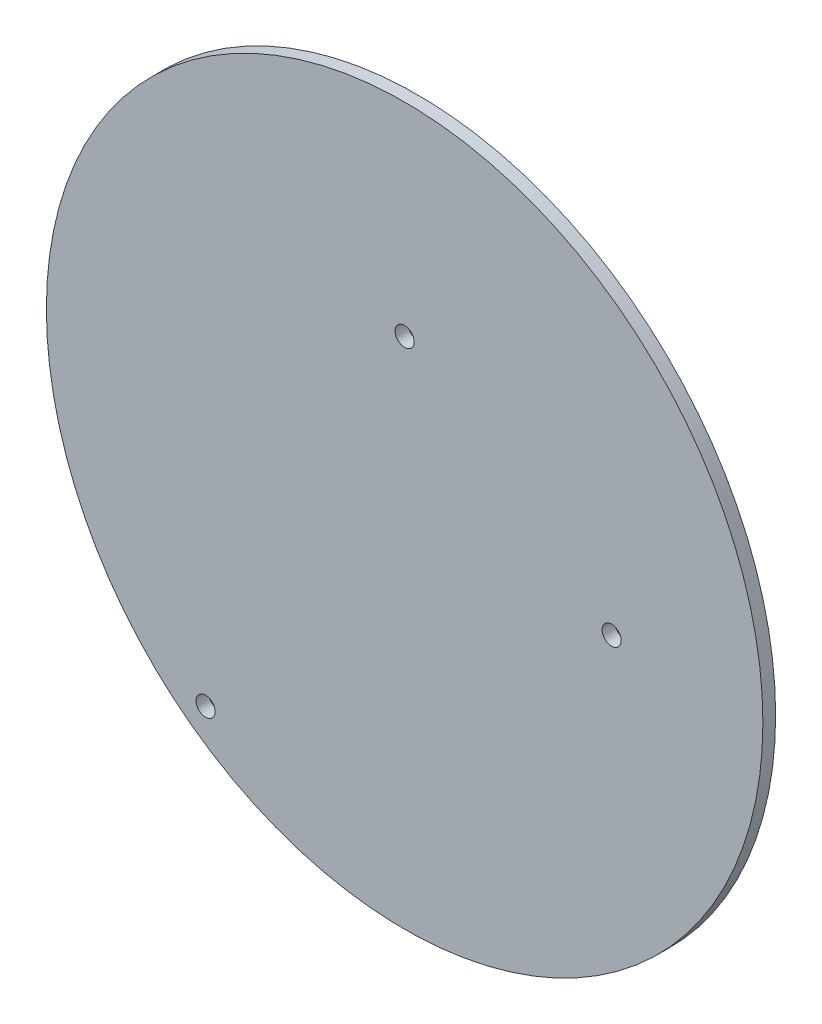
SolidWorks part; units mm, degrees
ref_plane "Front Plane" through (0, 0, 0) normal (1, 0, 0) x (0, 1, 0)
ref_plane "Top Plane" through (0, 0, 0) normal (0, 0, 1) x (0, 1, 0)
ref_plane "Right Plane" through (0, 0, 0) normal (0, 1, 0) x (-1, 0, 0)
sketch "Sketch5" plane through (0, 0, 0) normal (0, 0, 1) x (0, 1, 0)
  circle A0 centre (0, 0) radius 45
  dimension "D1" = 90
extrude "Boss-Extrude2" add sketch "Sketch5" along normal blind 1.6
sketch "Sketch2" plane through (0, 0, 0) normal (0, 0, 1) x (0, 1, 0)
  line L0 (19.5, 0) -> (0, 0) construction
  line L1 (0, 0) -> (0, -26) construction
  circle A0 centre (0, 0) radius 45
  point P0 (-42, -26)
  point P1 (0, -26)
  point P2 (19.5, 0)
  point P3 (-33.2215, 25)
  dimension "D6" = 90
  dimension "D1" = 42
  dimension "D2" = 61.5
  dimension "D3" = 26
  dimension "D4" = 51
  dimension "D5" = 51.75
hole_wizard "M2 Clearance Hole2" positions "Sketch2" profile "Sketch7" hole size "M2" standard "ANSI Metric"
sketch "Sketch7" plane through (-25, -33.2215, 0) normal (1, 0, 0) x (0, 1, 0)
  line L0 (0, 0) -> (0, 2.321)
  line L1 (0, 2.321) -> (1.2, 1.6)
  line L2 (1.2, 1.6) -> (1.2, 0)
  line L5 (1.2, 0) -> (0, 0)
  line L10 (0, 2.321) -> (-1.2, 1.6) construction
  line L11 (0, -6.35) -> (0, 107.95) construction
  dimension "Hole Dia." = 2.4
  dimension "Hole Depth" = 1.6
  dimension "Drill Angle" = 118
